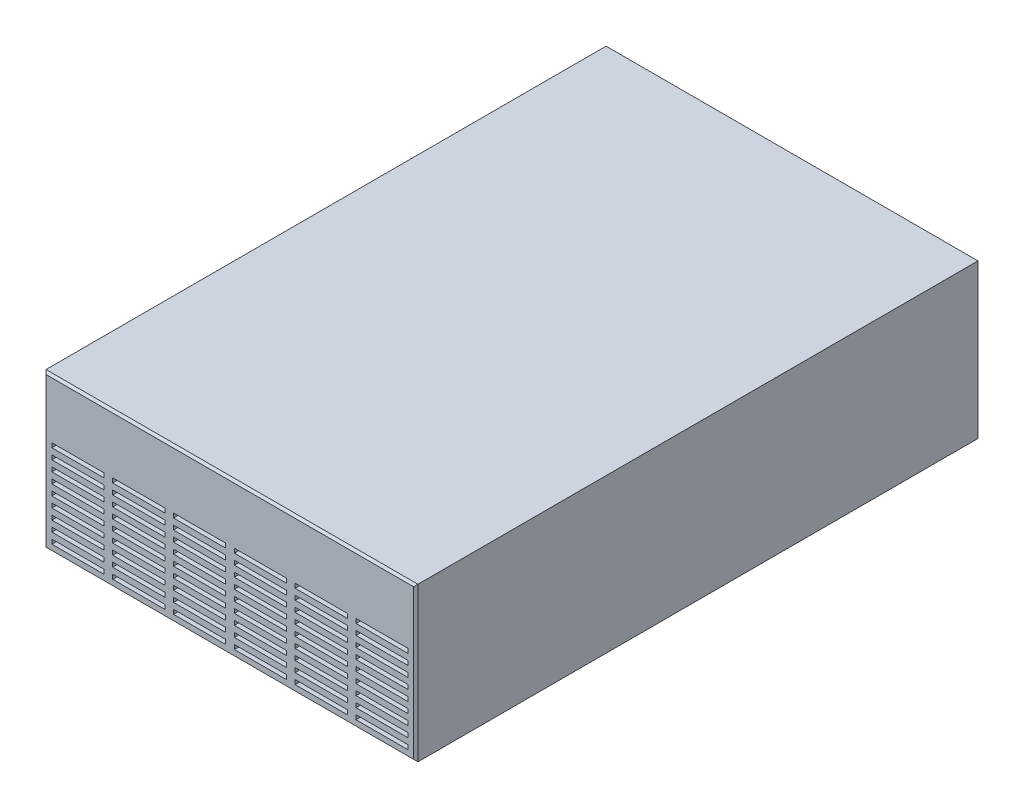
SolidWorks part; units mm, degrees
material "PVC Rigid"
ref_plane "Front Plane" through (0, 0, 0) normal (0, 0, 1) x (1, 0, 0)
ref_plane "Top Plane" through (0, 0, 0) normal (0, 1, 0) x (1, 0, 0)
ref_plane "Right Plane" through (0, 0, 0) normal (1, 0, 0) x (0, 0, -1)
sketch "Sketch1" plane through (0, 0, 0) normal (0, 0, 1) x (1, 0, 0)
  line L1 (0, 0) -> (428, 0)
  line L2 (0, 0) -> (0, 177)
  line L3 (0, 177) -> (428, 177)
  line L4 (428, 0) -> (428, 177)
  dimension "D1" = 177
  dimension "D2" = 428
extrude "Boss-Extrude1" add sketch "Sketch1" against normal blind 647
sketch "Sketch2" plane through (0, 0, 0) normal (0, 0, 1) x (1, 0, 0)
  line L0 (79.2658, 13.856) -> (79.2658, 8.856)
  line L1 (9.2658, 13.856) -> (69.2658, 13.856)
  line L2 (9.2658, 13.856) -> (9.2658, 8.856)
  line L3 (9.2658, 8.856) -> (69.2658, 8.856)
  line L4 (69.2658, 13.856) -> (69.2658, 8.856)
  line L5 (79.2658, 13.856) -> (139.2658, 13.856)
  line L6 (139.2658, 13.856) -> (139.2658, 8.856)
  line L7 (79.2658, 8.856) -> (139.2658, 8.856)
  line L8 (149.2658, 13.856) -> (149.2658, 8.856)
  line L9 (149.2658, 13.856) -> (209.2658, 13.856)
  line L10 (209.2658, 13.856) -> (209.2658, 8.856)
  line L11 (149.2658, 8.856) -> (209.2658, 8.856)
  line L12 (219.2658, 13.856) -> (219.2658, 8.856)
  line L13 (219.2658, 13.856) -> (279.2658, 13.856)
  line L14 (279.2658, 13.856) -> (279.2658, 8.856)
  line L15 (219.2658, 8.856) -> (279.2658, 8.856)
  line L16 (289.2658, 13.856) -> (289.2658, 8.856)
  line L17 (289.2658, 13.856) -> (349.2658, 13.856)
  line L18 (349.2658, 13.856) -> (349.2658, 8.856)
  line L19 (289.2658, 8.856) -> (349.2658, 8.856)
  line L20 (359.2658, 13.856) -> (359.2658, 8.856)
  line L21 (359.2658, 13.856) -> (419.2658, 13.856)
  line L22 (419.2658, 13.856) -> (419.2658, 8.856)
  line L23 (359.2658, 8.856) -> (419.2658, 8.856)
  line L24 (79.2658, 25.856) -> (79.2658, 20.856)
  line L25 (79.2658, 25.856) -> (139.2658, 25.856)
  line L26 (139.2658, 25.856) -> (139.2658, 20.856)
  line L27 (79.2658, 20.856) -> (139.2658, 20.856)
  line L28 (149.2658, 25.856) -> (149.2658, 20.856)
  line L29 (149.2658, 25.856) -> (209.2658, 25.856)
  line L30 (209.2658, 25.856) -> (209.2658, 20.856)
  line L31 (149.2658, 20.856) -> (209.2658, 20.856)
  line L32 (219.2658, 25.856) -> (219.2658, 20.856)
  line L33 (219.2658, 25.856) -> (279.2658, 25.856)
  line L34 (279.2658, 25.856) -> (279.2658, 20.856)
  line L35 (219.2658, 20.856) -> (279.2658, 20.856)
  line L36 (289.2658, 25.856) -> (289.2658, 20.856)
  line L37 (289.2658, 25.856) -> (349.2658, 25.856)
  line L38 (349.2658, 25.856) -> (349.2658, 20.856)
  line L39 (289.2658, 20.856) -> (349.2658, 20.856)
  line L40 (359.2658, 25.856) -> (359.2658, 20.856)
  line L41 (359.2658, 25.856) -> (419.2658, 25.856)
  line L42 (419.2658, 25.856) -> (419.2658, 20.856)
  line L43 (359.2658, 20.856) -> (419.2658, 20.856)
  line L44 (79.2658, 37.856) -> (79.2658, 32.856)
  line L45 (79.2658, 37.856) -> (139.2658, 37.856)
  line L46 (139.2658, 37.856) -> (139.2658, 32.856)
  line L47 (79.2658, 32.856) -> (139.2658, 32.856)
  line L48 (149.2658, 37.856) -> (149.2658, 32.856)
  line L49 (149.2658, 37.856) -> (209.2658, 37.856)
  line L50 (209.2658, 37.856) -> (209.2658, 32.856)
  line L51 (149.2658, 32.856) -> (209.2658, 32.856)
  line L52 (219.2658, 37.856) -> (219.2658, 32.856)
  line L53 (219.2658, 37.856) -> (279.2658, 37.856)
  line L54 (279.2658, 37.856) -> (279.2658, 32.856)
  line L55 (219.2658, 32.856) -> (279.2658, 32.856)
  line L56 (289.2658, 37.856) -> (289.2658, 32.856)
  line L57 (289.2658, 37.856) -> (349.2658, 37.856)
  line L58 (349.2658, 37.856) -> (349.2658, 32.856)
  line L59 (289.2658, 32.856) -> (349.2658, 32.856)
  line L60 (359.2658, 37.856) -> (359.2658, 32.856)
  line L61 (359.2658, 37.856) -> (419.2658, 37.856)
  line L62 (419.2658, 37.856) -> (419.2658, 32.856)
  line L63 (359.2658, 32.856) -> (419.2658, 32.856)
  line L64 (79.2658, 49.856) -> (79.2658, 44.856)
  line L65 (79.2658, 49.856) -> (139.2658, 49.856)
  line L66 (139.2658, 49.856) -> (139.2658, 44.856)
  line L67 (79.2658, 44.856) -> (139.2658, 44.856)
  line L68 (149.2658, 49.856) -> (149.2658, 44.856)
  line L69 (149.2658, 49.856) -> (209.2658, 49.856)
  line L70 (209.2658, 49.856) -> (209.2658, 44.856)
  line L71 (149.2658, 44.856) -> (209.2658, 44.856)
  line L72 (219.2658, 49.856) -> (219.2658, 44.856)
  line L73 (219.2658, 49.856) -> (279.2658, 49.856)
  line L74 (279.2658, 49.856) -> (279.2658, 44.856)
  line L75 (219.2658, 44.856) -> (279.2658, 44.856)
  line L76 (289.2658, 49.856) -> (289.2658, 44.856)
  line L77 (289.2658, 49.856) -> (349.2658, 49.856)
  line L78 (349.2658, 49.856) -> (349.2658, 44.856)
  line L79 (289.2658, 44.856) -> (349.2658, 44.856)
  line L80 (359.2658, 49.856) -> (359.2658, 44.856)
  line L81 (359.2658, 49.856) -> (419.2658, 49.856)
  line L82 (419.2658, 49.856) -> (419.2658, 44.856)
  line L83 (359.2658, 44.856) -> (419.2658, 44.856)
  line L84 (79.2658, 61.856) -> (79.2658, 56.856)
  line L85 (79.2658, 61.856) -> (139.2658, 61.856)
  line L86 (139.2658, 61.856) -> (139.2658, 56.856)
  line L87 (79.2658, 56.856) -> (139.2658, 56.856)
  line L88 (149.2658, 61.856) -> (149.2658, 56.856)
  line L89 (149.2658, 61.856) -> (209.2658, 61.856)
  line L90 (209.2658, 61.856) -> (209.2658, 56.856)
  line L91 (149.2658, 56.856) -> (209.2658, 56.856)
  line L92 (219.2658, 61.856) -> (219.2658, 56.856)
  line L93 (219.2658, 61.856) -> (279.2658, 61.856)
  line L94 (279.2658, 61.856) -> (279.2658, 56.856)
  line L95 (219.2658, 56.856) -> (279.2658, 56.856)
  line L96 (289.2658, 61.856) -> (289.2658, 56.856)
  line L97 (289.2658, 61.856) -> (349.2658, 61.856)
  line L98 (349.2658, 61.856) -> (349.2658, 56.856)
  line L99 (289.2658, 56.856) -> (349.2658, 56.856)
  line L100 (359.2658, 61.856) -> (359.2658, 56.856)
  line L101 (359.2658, 61.856) -> (419.2658, 61.856)
  line L102 (419.2658, 61.856) -> (419.2658, 56.856)
  line L103 (359.2658, 56.856) -> (419.2658, 56.856)
  line L104 (79.2658, 73.856) -> (79.2658, 68.856)
  line L105 (79.2658, 73.856) -> (139.2658, 73.856)
  line L106 (139.2658, 73.856) -> (139.2658, 68.856)
  line L107 (79.2658, 68.856) -> (139.2658, 68.856)
  line L108 (149.2658, 73.856) -> (149.2658, 68.856)
  line L109 (149.2658, 73.856) -> (209.2658, 73.856)
  line L110 (209.2658, 73.856) -> (209.2658, 68.856)
  line L111 (149.2658, 68.856) -> (209.2658, 68.856)
  line L112 (219.2658, 73.856) -> (219.2658, 68.856)
  line L113 (219.2658, 73.856) -> (279.2658, 73.856)
  line L114 (279.2658, 73.856) -> (279.2658, 68.856)
  line L115 (219.2658, 68.856) -> (279.2658, 68.856)
  line L116 (289.2658, 73.856) -> (289.2658, 68.856)
  line L117 (289.2658, 73.856) -> (349.2658, 73.856)
  line L118 (349.2658, 73.856) -> (349.2658, 68.856)
  line L119 (289.2658, 68.856) -> (349.2658, 68.856)
  line L120 (359.2658, 73.856) -> (359.2658, 68.856)
  line L121 (359.2658, 73.856) -> (419.2658, 73.856)
  line L122 (419.2658, 73.856) -> (419.2658, 68.856)
  line L123 (359.2658, 68.856) -> (419.2658, 68.856)
  line L124 (79.2658, 85.856) -> (79.2658, 80.856)
  line L125 (79.2658, 85.856) -> (139.2658, 85.856)
  line L126 (139.2658, 85.856) -> (139.2658, 80.856)
  line L127 (79.2658, 80.856) -> (139.2658, 80.856)
  line L128 (149.2658, 85.856) -> (149.2658, 80.856)
  line L129 (149.2658, 85.856) -> (209.2658, 85.856)
  line L130 (209.2658, 85.856) -> (209.2658, 80.856)
  line L131 (149.2658, 80.856) -> (209.2658, 80.856)
  line L132 (219.2658, 85.856) -> (219.2658, 80.856)
  line L133 (219.2658, 85.856) -> (279.2658, 85.856)
  line L134 (279.2658, 85.856) -> (279.2658, 80.856)
  line L135 (219.2658, 80.856) -> (279.2658, 80.856)
  line L136 (289.2658, 85.856) -> (289.2658, 80.856)
  line L137 (289.2658, 85.856) -> (349.2658, 85.856)
  line L138 (349.2658, 85.856) -> (349.2658, 80.856)
  line L139 (289.2658, 80.856) -> (349.2658, 80.856)
  line L140 (359.2658, 85.856) -> (359.2658, 80.856)
  line L141 (359.2658, 85.856) -> (419.2658, 85.856)
  line L142 (419.2658, 85.856) -> (419.2658, 80.856)
  line L143 (359.2658, 80.856) -> (419.2658, 80.856)
  line L144 (79.2658, 97.856) -> (79.2658, 92.856)
  line L145 (79.2658, 97.856) -> (139.2658, 97.856)
  line L146 (139.2658, 97.856) -> (139.2658, 92.856)
  line L147 (79.2658, 92.856) -> (139.2658, 92.856)
  line L148 (149.2658, 97.856) -> (149.2658, 92.856)
  line L149 (149.2658, 97.856) -> (209.2658, 97.856)
  line L150 (209.2658, 97.856) -> (209.2658, 92.856)
  line L151 (149.2658, 92.856) -> (209.2658, 92.856)
  line L152 (219.2658, 97.856) -> (219.2658, 92.856)
  line L153 (219.2658, 97.856) -> (279.2658, 97.856)
  line L154 (279.2658, 97.856) -> (279.2658, 92.856)
  line L155 (219.2658, 92.856) -> (279.2658, 92.856)
  line L156 (289.2658, 97.856) -> (289.2658, 92.856)
  line L157 (289.2658, 97.856) -> (349.2658, 97.856)
  line L158 (349.2658, 97.856) -> (349.2658, 92.856)
  line L159 (289.2658, 92.856) -> (349.2658, 92.856)
  line L160 (359.2658, 97.856) -> (359.2658, 92.856)
  line L161 (359.2658, 97.856) -> (419.2658, 97.856)
  line L162 (419.2658, 97.856) -> (419.2658, 92.856)
  line L163 (359.2658, 92.856) -> (419.2658, 92.856)
  line L164 (79.2658, 109.856) -> (79.2658, 104.856)
  line L165 (79.2658, 109.856) -> (139.2658, 109.856)
  line L166 (139.2658, 109.856) -> (139.2658, 104.856)
  line L167 (79.2658, 104.856) -> (139.2658, 104.856)
  line L168 (149.2658, 109.856) -> (149.2658, 104.856)
  line L169 (149.2658, 109.856) -> (209.2658, 109.856)
  line L170 (209.2658, 109.856) -> (209.2658, 104.856)
  line L171 (149.2658, 104.856) -> (209.2658, 104.856)
  line L172 (219.2658, 109.856) -> (219.2658, 104.856)
  line L173 (219.2658, 109.856) -> (279.2658, 109.856)
  line L174 (279.2658, 109.856) -> (279.2658, 104.856)
  line L175 (219.2658, 104.856) -> (279.2658, 104.856)
  line L176 (289.2658, 109.856) -> (289.2658, 104.856)
  line L177 (289.2658, 109.856) -> (349.2658, 109.856)
  line L178 (349.2658, 109.856) -> (349.2658, 104.856)
  line L179 (289.2658, 104.856) -> (349.2658, 104.856)
  line L180 (359.2658, 109.856) -> (359.2658, 104.856)
  line L181 (359.2658, 109.856) -> (419.2658, 109.856)
  line L182 (419.2658, 109.856) -> (419.2658, 104.856)
  line L183 (359.2658, 104.856) -> (419.2658, 104.856)
  line L184 (9.2658, 25.856) -> (9.2658, 20.856)
  line L185 (9.2658, 25.856) -> (69.2658, 25.856)
  line L186 (69.2658, 25.856) -> (69.2658, 20.856)
  line L187 (9.2658, 20.856) -> (69.2658, 20.856)
  line L188 (9.2658, 37.856) -> (9.2658, 32.856)
  line L189 (9.2658, 37.856) -> (69.2658, 37.856)
  line L190 (69.2658, 37.856) -> (69.2658, 32.856)
  line L191 (9.2658, 32.856) -> (69.2658, 32.856)
  line L192 (9.2658, 49.856) -> (9.2658, 44.856)
  line L193 (9.2658, 49.856) -> (69.2658, 49.856)
  line L194 (69.2658, 49.856) -> (69.2658, 44.856)
  line L195 (9.2658, 44.856) -> (69.2658, 44.856)
  line L196 (9.2658, 61.856) -> (9.2658, 56.856)
  line L197 (9.2658, 61.856) -> (69.2658, 61.856)
  line L198 (69.2658, 61.856) -> (69.2658, 56.856)
  line L199 (9.2658, 56.856) -> (69.2658, 56.856)
  line L200 (9.2658, 73.856) -> (9.2658, 68.856)
  line L201 (9.2658, 73.856) -> (69.2658, 73.856)
  line L202 (69.2658, 73.856) -> (69.2658, 68.856)
  line L203 (9.2658, 68.856) -> (69.2658, 68.856)
  line L204 (9.2658, 85.856) -> (9.2658, 80.856)
  line L205 (9.2658, 85.856) -> (69.2658, 85.856)
  line L206 (69.2658, 85.856) -> (69.2658, 80.856)
  line L207 (9.2658, 80.856) -> (69.2658, 80.856)
  line L208 (9.2658, 97.856) -> (9.2658, 92.856)
  line L209 (9.2658, 97.856) -> (69.2658, 97.856)
  line L210 (69.2658, 97.856) -> (69.2658, 92.856)
  line L211 (9.2658, 92.856) -> (69.2658, 92.856)
  line L212 (9.2658, 109.856) -> (9.2658, 104.856)
  line L213 (9.2658, 109.856) -> (69.2658, 109.856)
  line L214 (69.2658, 109.856) -> (69.2658, 104.856)
  line L215 (9.2658, 104.856) -> (69.2658, 104.856)
  dimension "D1" = 5
  dimension "D2" = 60
  dimension "D3" = 6
  dimension "D4" = 9
extrude "Cut-Extrude1" cut sketch "Sketch2" against normal blind 5
chamfer "Chamfer1" distance 2.5 angle 45 4 edges at (214, 0, 0) (0, 88.5, 0) (428, 88.5, 0) (214, 177, 0)
